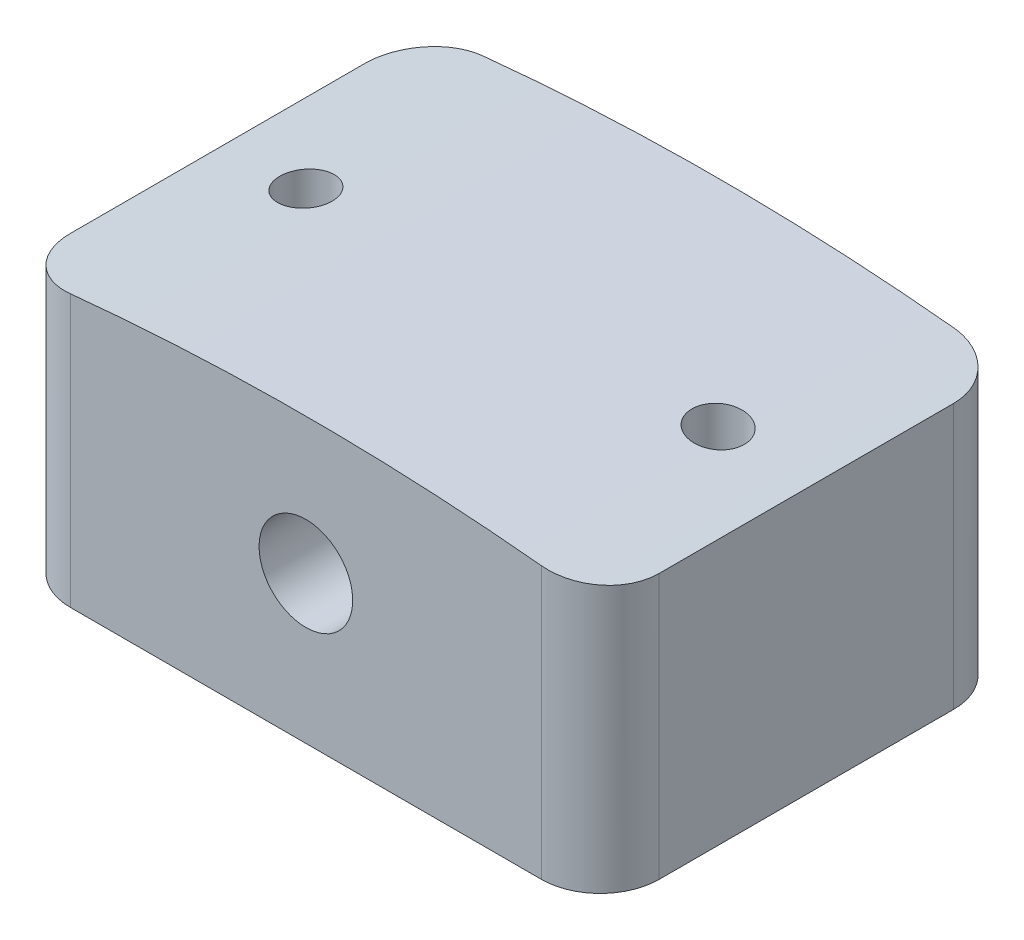
SolidWorks part; units mm, degrees
ref_plane "Front Plane" through (0, 0, 0) normal (0, 0, 1) x (1, 0, 0)
ref_plane "Top Plane" through (0, 0, 0) normal (0, 1, 0) x (1, 0, 0)
ref_plane "Right Plane" through (0, 0, 0) normal (1, 0, 0) x (0, 0, -1)
sketch "Sketch1" plane through (0, 0, 0) normal (0, 0, 1) x (1, 0, 0)
  line L2 (12.6987, 100.8033) -> (12.6987, 89.3733)
  line L3 (12.6987, 89.3733) -> (-12.6987, 89.3733)
  line L4 (-12.6987, 89.3733) -> (-12.6987, 100.8033)
  arc A1 (12.6987, 100.8033) -> (-12.6987, 100.8033) centre (0, 0) ccw
extrude "Boss-Extrude1" add sketch "Sketch1" along normal blind 8.89 and the other way blind 8.89
sketch "Sketch12" plane through (0, 89.3733, 0) normal (0, -1, 0) x (1, 0, 0)
  circle A0 centre (0, 0) radius 3.175
hole_wizard "1/4 (0.25) Diameter Slot1" positions "Sketch14" profile "Sketch13" size "1/4" standard "ANSI Inch" slot yes
sketch "Sketch14" plane through (0, 89.3733, 0) normal (0, -1, 0) x (-1, 0, 0)
  point P0 (0, 0)
sketch "Sketch13" plane through (0, 89.3733, 0) normal (1, 0, 0) x (0, 0, -1)
  line L0 (0, 0) -> (0, 11.5597)
  line L1 (0, 11.5597) -> (3.175, 9.652)
  line L2 (3.175, 9.652) -> (3.175, 0)
  line L5 (3.175, 0) -> (0, 0)
  line L10 (0, 11.5597) -> (-3.175, 9.652) construction
  line L11 (0, -6.35) -> (0, 107.95) construction
  dimension "Hole Dia." = 6.35
  dimension "Hole Depth" = 9.652
  dimension "Drill Angle" = 118
sketch "Sketch15" plane through (0, 89.3733, 0) normal (0, -1, 0) x (1, 0, 0)
  line L0 (-12.6987, -8.89) -> (-12.6987, 8.89) construction
  line L1 (12.6987, -8.89) -> (12.6987, 8.89) construction
  circle A0 centre (-8.8887, 0) radius 1.4224
  circle A1 centre (8.8887, 0) radius 1.4224
  dimension "D1" = 3.81
  dimension "D2" = 3.81
hole_wizard "Tap Drill for #4-40 Tap2" positions "Sketch17" profile "Sketch18" hole size "#4-40" standard "ANSI Inch" end condition through all
sketch "Sketch17" plane through (0, 89.3733, 0) normal (0, -1, 0) x (-1, 0, 0)
  point P0 (8.8887, 0)
  point P3 (-8.8887, 0)
sketch "Sketch18" plane through (-8.8887, 89.3733, 0) normal (1, 0, 0) x (0, 0, -1)
  line L0 (0, 0) -> (0, 12.2267)
  line L1 (0, 12.2267) -> (1.1303, 12.2267)
  line L2 (1.1303, 12.2267) -> (1.1303, 0)
  line L5 (1.1303, 0) -> (0, 0)
  line L11 (0, -6.35) -> (0, 107.95) construction
  dimension "Thru Hole Dia." = 2.2606
  dimension "Thru Hole Depth" = 12.2267
fillet "Fillet1" radius 2.54 4 edges at (12.6987, 95.0883, -8.89) (12.6987, 95.0883, 8.89) (-12.6987, 95.0883, -8.89) (-12.6987, 95.0883, 8.89)
sketch "Sketch19" plane through (0, 0, -8.89) normal (0, 0, -1) x (-1, 0, 0)
  line L0 (10.1587, 89.3733) -> (-10.1587, 89.3733) construction
  point P0 (0, 95.7233)
  dimension "D1" = 6.35
hole_wizard "#10-32 Tapped Hole1" positions "Sketch21" profile "Sketch20" tap size "#10-32" standard "ANSI Inch" end condition through all
sketch "Sketch21" plane through (0, 0, -8.89) normal (0, 0, -1) x (-1, 0, 0)
  point P0 (0, 95.7233)
sketch "Sketch20" plane through (0, 95.7233, -8.89) normal (1, 0, 0) x (0, 1, 0)
  line L0 (0, 0) -> (0, 17.78)
  line L1 (0, 17.78) -> (2.0193, 17.78)
  line L2 (2.0193, 17.78) -> (2.0193, 0)
  line L5 (2.0193, 0) -> (0, 0)
  line L11 (0, -6.35) -> (0, 107.95) construction
  dimension "Thread Major Dia." = 4.0386
  dimension "Thru Tap Drill Depth" = 17.78
